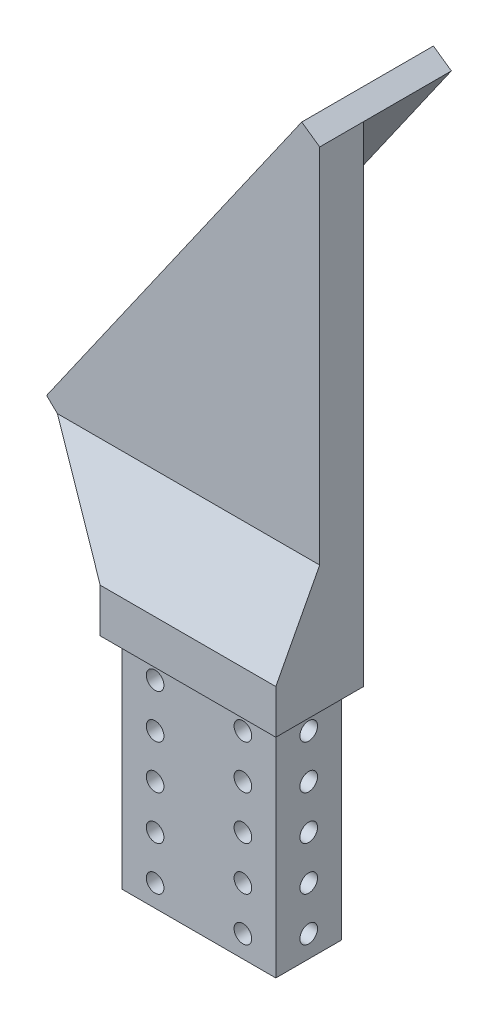
SolidWorks part; units mm, degrees
material "6061-T6 (SS)"
ref_plane "Front Plane" through (0, 0, 0) normal (0, 0, 1) x (1, 0, 0)
ref_plane "Top Plane" through (0, 0, 0) normal (0, 1, 0) x (1, 0, 0)
ref_plane "Right Plane" through (0, 0, 0) normal (1, 0, 0) x (0, 0, -1)
sketch "Sketch1" plane through (0, 0, 0) normal (0, 0, 1) x (1, 0, 0)
  line L0 (50.8, 76.2) -> (152.4, 76.2)
  line L1 (0, 0) -> (50.8, 0)
  line L2 (0, 0) -> (0, 76.2)
  line L4 (50.8, 0) -> (50.8, 76.2)
  line L5 (-101.6, 76.2) -> (0, 76.2)
  line L6 (-101.6, 76.2) -> (-101.6, 254)
  line L7 (-101.6, 254) -> (152.4, 254)
  line L8 (152.4, 76.2) -> (152.4, 254)
  dimension "D1" = 50.8
  dimension "D2" = 76.2
  dimension "D3" = 254
  dimension "D4" = 177.8
extrude "Boss-Extrude1" add sketch "Sketch1" along normal blind 25.4
sketch "Sketch3" plane through (0, 0, 25.4) normal (0, 0, 1) x (1, 0, 0)
  line L0 (50.8, 0) -> (50.8, 76.2) construction
  line L1 (0, 0) -> (50.8, 0)
  line L2 (0, 0) -> (0, 63.5)
  line L3 (0, 63.5) -> (50.8, 63.5)
  line L4 (50.8, 0) -> (50.8, 63.5)
  dimension "D1" = 63.5
sketch "Sketch4" plane through (0, 0, 0) normal (-1, 0, 0) x (0, 0, 1)
  line L0 (25.4, 0) -> (25.4, 63.5) construction
  line L1 (0, 0) -> (25.4, 0)
  line L2 (0, 0) -> (0, 63.5)
  line L3 (0, 63.5) -> (25.4, 63.5)
  line L4 (25.4, 0) -> (25.4, 63.5)
  dimension "D1" = 63.5
sketch "Sketch5" plane through (0, 0, 0) normal (0, 0, -1) x (-1, 0, 0)
  line L1 (0, 0) -> (-50.8, 0)
  line L2 (0, 0) -> (0, 63.5)
  line L3 (0, 63.5) -> (-50.8, 63.5)
  line L4 (-50.8, 0) -> (-50.8, 63.5)
sketch "Sketch6" plane through (50.8, 0, 0) normal (1, 0, 0) x (0, 0, -1)
  line L1 (0, 0) -> (-25.4, 0)
  line L2 (0, 0) -> (0, 63.5)
  line L3 (0, 63.5) -> (-25.4, 63.5)
  line L4 (-25.4, 0) -> (-25.4, 63.5)
extrude "Cut-Extrude1" cut sketch "Sketch3" against normal blind 3.175
extrude "Cut-Extrude2" cut sketch "Sketch4" against normal blind 3.175
extrude "Cut-Extrude3" cut sketch "Sketch5" against normal blind 3.175
extrude "Cut-Extrude4" cut sketch "Sketch6" against normal blind 3.175
sketch "Sketch7" plane through (0, 0, 25.4) normal (0, 0, 1) x (1, 0, 0)
  line L0 (50.8, 76.2) -> (50.8, 254)
  line L4 (152.4, 254) -> (-101.6, 254) construction
  line L5 (50.8, 76.2) -> (152.4, 76.2)
  line L6 (152.4, 76.2) -> (152.4, 254)
  line L7 (152.4, 254) -> (50.8, 254)
extrude "Cut-Extrude5" cut sketch "Sketch7" against normal through all
sketch "Sketch9" plane through (0, 0, 25.4) normal (0, 0, 1) x (1, 0, 0)
  line L0 (34.6576, 254) -> (50.8, 254)
  line L1 (50.8, 254) -> (-101.6, 254) construction
  line L2 (50.8, 254) -> (50.8, 242.697)
  line L3 (50.8, 242.697) -> (34.6576, 254)
  line L4 (50.8, 63.5) -> (50.8, 254) construction
  dimension "D1" = 11.303
  dimension "D2" = 35
extrude "Cut-Extrude7" cut sketch "Sketch9" against normal through all
sketch "Sketch8" plane through (0, 0, 25.4) normal (0, 0, 1) x (1, 0, 0)
  line L2 (34.6576, 254) -> (-101.6, 254) construction
  line L12 (34.6576, 254) -> (-101.6, 59.4039)
  line L13 (-101.6, 59.4039) -> (-101.6, 254)
  line L14 (-101.6, 254) -> (34.6576, 254)
  dimension "D1" = 55
extrude "Cut-Extrude6" cut sketch "Sketch8" against normal through all
sketch "Sketch10" plane through (0, 0, 25.4) normal (0, 0, 1) x (1, 0, 0)
  line L0 (34.6576, 254) -> (45.5977, 246.3397)
  line L1 (34.6576, 254) -> (50.8, 242.697) construction
  line L2 (45.5977, 246.3397) -> (-84.0298, 61.2124)
  line L4 (-84.0298, 61.2124) -> (-94.9699, 68.8727)
  line L5 (-94.9699, 68.8727) -> (34.6576, 254)
  line L6 (-89.8393, 76.2) -> (34.6576, 254) construction
  dimension "D1" = 13.3553
  dimension "D2" = 13.3553
  dimension "D3" = 225.9987
extrude "Cut-Extrude8" cut sketch "Sketch10" against normal through all
sketch "Sketch11" plane through (0, 0, 22.225) normal (0, 0, 1) x (1, 0, 0)
  line L1 (50.8, 63.5) -> (0, 63.5) construction
  line L2 (47.625, 63.5) -> (3.175, 63.5) construction
  line L3 (3.175, 63.5) -> (3.175, 0) construction
  circle A0 centre (12.7, 57.15) radius 2.5527
  circle A1 centre (12.7, 44.45) radius 2.5527
  circle A2 centre (12.7, 31.75) radius 2.5527
  circle A3 centre (12.7, 19.05) radius 2.5527
  circle A4 centre (12.7, 6.35) radius 2.5527
  circle A5 centre (38.1, 44.45) radius 2.5527
  circle A6 centre (38.1, 31.75) radius 2.5527
  circle A7 centre (38.1, 19.05) radius 2.5527
  circle A8 centre (38.1, 6.35) radius 2.5527
  circle A9 centre (38.1, 57.15) radius 2.5527
  dimension "D1" = 5.1054
  dimension "D2" = 9.525
  dimension "D3" = 6.35
  dimension "D6" = 25.4
  dimension "D7" = 12.7
  dimension "D8" = 6.35
  dimension "D4" = 5
  dimension "D5" = 2
sketch "Sketch12" plane through (3.175, 0, 0) normal (-1, 0, 0) x (0, 0, 1)
  line L0 (0, 63.5) -> (25.4, 63.5) construction
  line L2 (3.175, 0) -> (3.175, 63.5) construction
  circle A0 centre (12.7, 57.15) radius 2.5527
  circle A1 centre (12.7, 44.45) radius 2.5527
  circle A2 centre (12.7, 31.75) radius 2.5527
  circle A3 centre (12.7, 19.05) radius 2.5527
  circle A4 centre (12.7, 6.35) radius 2.5527
  dimension "D1" = 6.35
  dimension "D2" = 9.525
  dimension "D3" = 5.1054
  dimension "D5" = 12.7
  dimension "D4" = 5
extrude "Cut-Extrude9" cut sketch "Sketch11" against normal through all
extrude "Cut-Extrude10" cut sketch "Sketch12" against normal through all
sketch "Sketch17" plane through (0, 0, 0) normal (0, 0, -1) x (-1, 0, 0)
  line L0 (-45.5977, 246.3397) -> (-68.4848, 230.314)
  line L1 (-45.5977, 246.3397) -> (-50.8, 242.697) construction
  line L2 (-68.4848, 230.314) -> (51.3025, 59.2401)
  line L3 (51.3025, 59.2401) -> (74.1896, 75.2658)
  line L4 (74.1896, 75.2658) -> (-45.5977, 246.3397)
  dimension "D1" = 27.94
extrude "Boss-Extrude2" add sketch "Sketch17" along normal blind 25.4
sketch "Sketch18" plane through (0, 0, -25.4) normal (0, 0, -1) x (-1, 0, 0)
  line L0 (39.427, 76.2) -> (73.5354, 76.2)
  line L1 (73.5354, 76.2) -> (74.1896, 75.2658)
  line L2 (74.1896, 75.2658) -> (51.3025, 59.2401)
  line L3 (51.3025, 59.2401) -> (39.427, 76.2)
extrude "Cut-Extrude11" cut sketch "Sketch18" against normal through all
sketch "Sketch19" plane through (0, 0, 25.4) normal (0, 0, 1) x (1, 0, 0)
  line L0 (0, 76.2) -> (-43.9727, 118.4199)
  line L1 (-73.5354, 76.2) -> (0, 76.2) construction
  line L2 (-73.5354, 76.2) -> (45.5977, 246.3397) construction
  line L3 (-43.9727, 118.4199) -> (-73.5354, 76.2)
  line L4 (-73.5354, 76.2) -> (0, 76.2)
  dimension "D1" = 60.96
extrude "Cut-Extrude12" cut sketch "Sketch19" against normal through all
sketch "Sketch20" plane through (50.8, 0, 0) normal (1, 0, 0) x (0, 0, -1)
  line L0 (-25.4, 76.2) -> (-12.7, 100.2897)
  line L1 (-25.4, 63.5) -> (-25.4, 242.697) construction
  line L2 (-12.7, 100.2897) -> (-12.7, 246.3397)
  line L3 (25.4, 246.3397) -> (-25.4, 246.3397) construction
  line L4 (-12.7, 246.3397) -> (-25.4, 246.3397)
  line L5 (-25.4, 246.3397) -> (-25.4, 76.2)
  dimension "D1" = 12.7
  dimension "D2" = 146.05
  dimension "D3" = 12.7
extrude "Cut-Extrude13" cut sketch "Sketch20" against normal through all
sketch "Sketch21" plane through (0, 0, -25.4) normal (0, 0, -1) x (-1, 0, 0)
  line L0 (-45.5977, 246.3397) -> (-63.2832, 233.9562)
  line L1 (-45.5977, 246.3397) -> (-68.4848, 230.314) construction
  line L2 (-63.2832, 233.9562) -> (28.212, 103.2875)
  line L3 (43.9727, 118.4199) -> (23.5765, 98.8368) construction
  line L4 (28.212, 103.2875) -> (45.8975, 115.671)
  line L5 (45.8975, 115.671) -> (-45.5977, 246.3397)
  dimension "D1" = 21.59
  dimension "D2" = 21.59
extrude "Cut-Extrude14" cut sketch "Sketch21" against normal through all
sketch "Sketch22" plane through (0, 0, -25.4) normal (0, 0, -1) x (-1, 0, 0)
  line L0 (-50.8, 205.0575) -> (-45.5977, 208.6987)
  line L3 (-45.5977, 208.6987) -> (-63.2832, 233.9562)
  line L4 (-63.2832, 233.9562) -> (-68.4848, 230.314)
  line L5 (-68.4848, 230.314) -> (-50.8, 205.0575)
extrude "Cut-Extrude15" cut sketch "Sketch22" against normal through all
